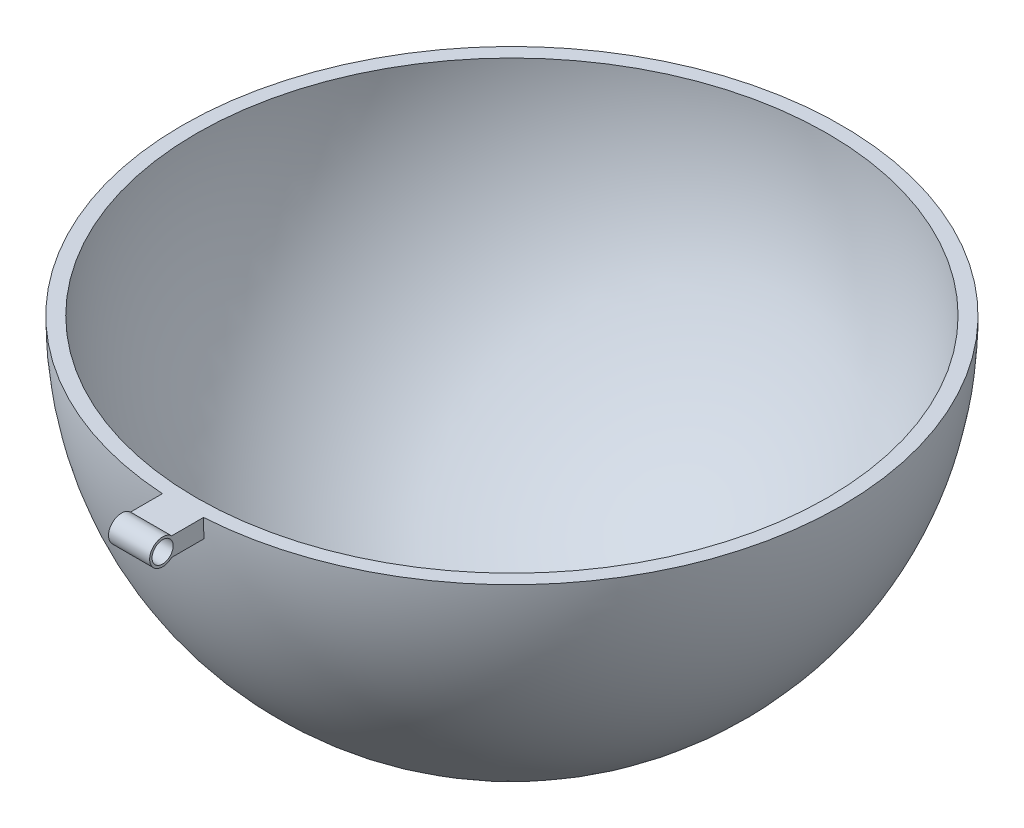
SolidWorks part; units mm, degrees
ref_plane "Front Plane" through (0, 0, 0) normal (0, 0, 1) x (1, 0, 0)
ref_plane "Top Plane" through (0, 0, 0) normal (0, 1, 0) x (1, 0, 0)
ref_plane "Right Plane" through (0, 0, 0) normal (1, 0, 0) x (0, 0, -1)
sketch "Sketch1" plane through (0, 0, 0) normal (0, 1, 0) x (1, 0, 0)
  line L0 (-79.375, 0) -> (-75.9776, 0)
  line L1 (75.9776, 0) -> (79.375, 0)
  arc A0 (-79.375, 0) -> (79.375, 0) centre (0, 0) ccw
  arc A1 (-75.9776, 0) -> (75.9776, 0) centre (0, 0) ccw
  dimension "D1" = 158.75
  dimension "D2" = 75.9776
revolve "Revolve1" add sketch "Sketch1" angle 180 about L0
sketch "Sketch2" plane through (0, 0, 0) normal (1, 0, 0) x (0, 0, -1)
  line L0 (-75.9776, 0) -> (-86.8996, 0)
  line L1 (-75.9776, 0) -> (-75.9776, -4.5084)
  line L2 (-75.9776, -4.5084) -> (-86.8996, -4.5084)
  circle A0 centre (-89.0678, -2.2542) radius 2.54
  arc A1 (-86.8996, 0) -> (-86.8996, -4.5084) centre (-89.0678, -2.2542) ccw
  dimension "D1" = 5.08
  dimension "D4" = 3.1277
  dimension "D2" = 10.922
  dimension "D3" = 10.922
  dimension "D5" = 89.0678
extrude "Boss-Extrude1" add sketch "Sketch2" along normal mid plane 9.906
